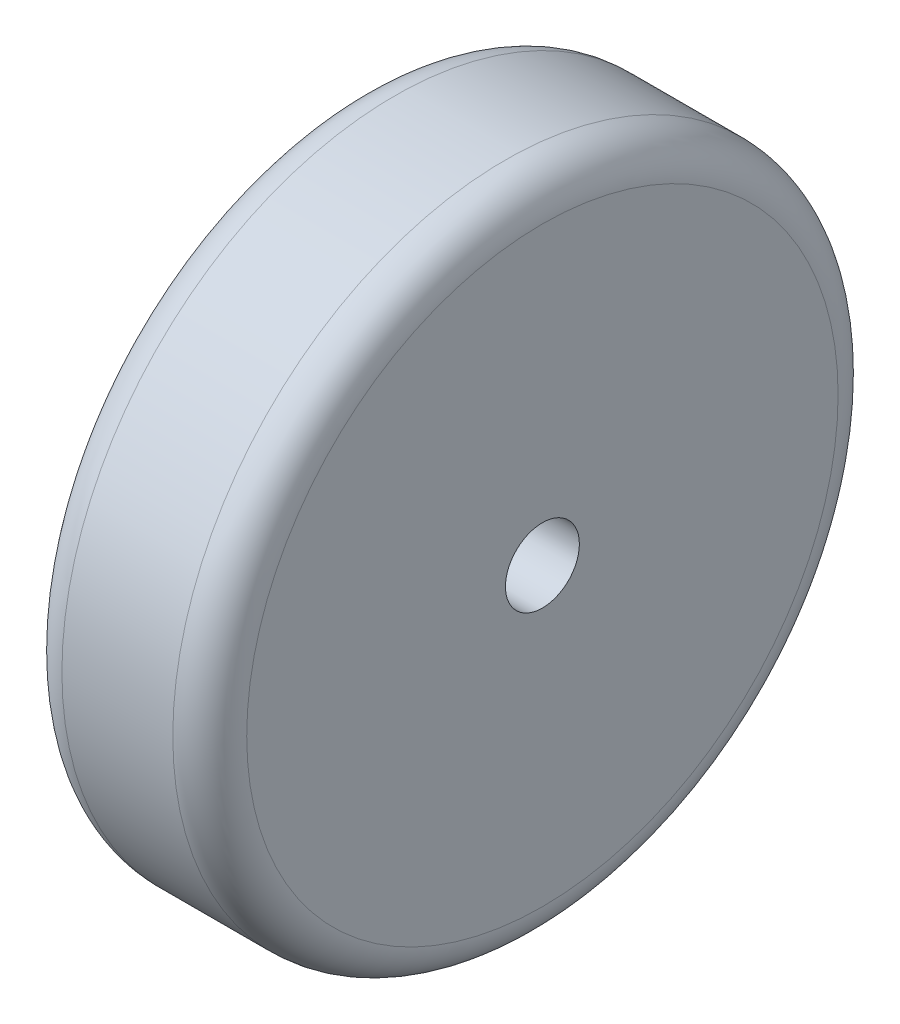
SolidWorks part; units mm, degrees
ref_plane "Alzado" through (0, 0, 0) normal (0, 0, 1) x (1, 0, 0)
ref_plane "Planta" through (0, 0, 0) normal (0, 1, 0) x (1, 0, 0)
ref_plane "Vista lateral" through (0, 0, 0) normal (1, 0, 0) x (0, 0, -1)
sketch "Croquis1" plane through (0, 0, 0) normal (1, 0, 0) x (0, 0, -1)
  circle A0 centre (0, 0) radius 90
  circle A1 centre (0, 0) radius 10
  dimension "D1" = 20
  dimension "D2" = 180
extrude "Saliente-Extruir1" add sketch "Croquis1" along normal mid plane 50
fillet "Redondeo1" radius 10 2 edges at (-25, 0, -90) (25, 0, -90)
